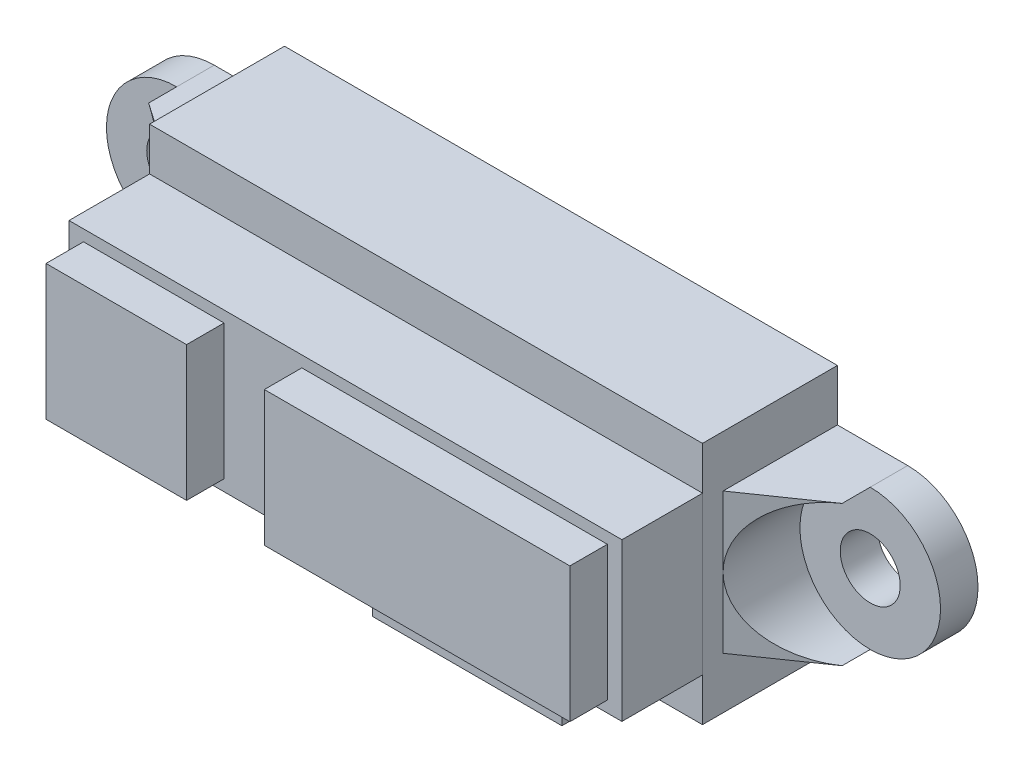
SolidWorks part; units mm, degrees
ref_plane "Front Plane" through (0, 0, 0) normal (0, 0, 1) x (1, 0, 0)
ref_plane "Top Plane" through (0, 0, 0) normal (0, 1, 0) x (1, 0, 0)
ref_plane "Right Plane" through (0, 0, 0) normal (1, 0, 0) x (0, 0, -1)
sketch "Sketch1" plane through (0, 0, 0) normal (0, 0, 1) x (1, 0, 0)
  line L1 (-14.75, 6.5) -> (14.75, 6.5)
  line L2 (-14.75, 6.5) -> (-14.75, -6.5)
  line L3 (-14.75, -6.5) -> (14.75, -6.5)
  line L4 (14.75, 6.5) -> (14.75, -6.5)
  line L5 (-14.75, 6.5) -> (14.75, -6.5) construction
  line L6 (-14.75, -6.5) -> (14.75, 6.5) construction
  point P0 (0, 0)
  dimension "D1" = 13
  dimension "D2" = 29.5
extrude "Boss-Extrude1" add sketch "Sketch1" along normal blind 7.2
sketch "Sketch2" plane through (0, 0, 7.2) normal (0, 0, 1) x (1, 0, 0)
  line L0 (14.75, -6.5) -> (14.75, 6.5) construction
  line L1 (-14.7465, 4.1995) -> (14.7535, 4.1995)
  line L2 (-14.7465, 4.1995) -> (-14.757, -4.2005)
  line L3 (-14.757, -4.2005) -> (14.75, -4.2005)
  line L4 (14.7535, 4.1995) -> (14.75, -4.2005)
  line L5 (-14.7465, 4.1995) -> (14.75, -4.2005) construction
  line L6 (-14.757, -4.2005) -> (14.7535, 4.1995) construction
  point P0 (0, 0)
  dimension "D1" = 29.5
  dimension "D2" = 8.4
extrude "Boss-Extrude2" add sketch "Sketch2" along normal blind 4.3
sketch "Sketch3" plane through (0, 0, 11.5) normal (0, 0, 1) x (1, 0, 0)
  line L1 (-13.975, 3.6) -> (13.975, 3.6) construction
  line L2 (-13.975, 3.6) -> (-13.975, -3.6) construction
  line L3 (-13.975, -3.6) -> (13.975, -3.6) construction
  line L4 (13.975, 3.6) -> (13.975, -3.6) construction
  line L5 (-13.975, 3.6) -> (13.975, -3.6) construction
  line L6 (-13.975, -3.6) -> (13.975, 3.6) construction
  line L7 (-13.975, 3.6) -> (-6.475, 3.6)
  line L8 (-13.975, 3.6) -> (-13.975, -3.6)
  line L9 (-13.975, -3.6) -> (-6.475, -3.6)
  line L10 (-6.475, 3.6) -> (-6.475, -3.6)
  line L11 (13.975, 3.6) -> (-2.325, 3.6)
  line L12 (13.975, 3.6) -> (13.975, -3.6)
  line L13 (13.975, -3.6) -> (-2.325, -3.6)
  line L14 (-2.325, 3.6) -> (-2.325, -3.6)
  point P1 (0, 0)
  dimension "D1" = 7.2
  dimension "D2" = 27.95
  dimension "D3" = 7.5
  dimension "D4" = 16.3
extrude "Boss-Extrude3" add sketch "Sketch3" along normal blind 2
sketch "Sketch4" plane through (0, 0, 0) normal (0, 0, -1) x (-1, 0, 0)
  line L0 (0, 6.5) -> (0, -6.5) construction
  line L1 (-14.75, 6.5) -> (14.75, 6.5) construction
  line L2 (14.75, -6.5) -> (-14.75, -6.5) construction
  line L3 (14.75, 6.5) -> (14.75, -6.5) construction
  line L5 (-14.75, 3.75) -> (-14.75, -3.75)
  line L6 (18.5, 3.75) -> (14.75, 3.75)
  line L7 (-18.5, -3.75) -> (-14.75, -3.75)
  line L8 (18.5, -3.75) -> (14.75, -3.75)
  line L9 (14.75, 3.75) -> (14.75, -3.75)
  line L10 (-18.5, 3.75) -> (-14.75, 3.75)
  arc A0 (18.5, -3.75) -> (18.5, 3.75) centre (18.5, 0) ccw
  arc A1 (-18.5, -3.75) -> (-18.5, 3.75) centre (-18.5, 0) cw
  circle A2 centre (18.5, 0) radius 1.6
  circle A3 centre (-18.5, 0) radius 1.6
  dimension "D2" = 3.75
  dimension "D1" = 7.5
  dimension "D5" = 3.2
  dimension "D3" = 6.5
  dimension "D4" = 7.5
extrude "Boss-Extrude6" add sketch "Sketch4" against normal blind 2
sketch "Sketch6" plane through (0, 0, 0) normal (0, 0, -1) x (-1, 0, 0)
  line L0 (14.75, -6.5) -> (-14.75, -6.5) construction
  line L1 (-5.05, -6.5) -> (5.05, -6.5)
  line L2 (-5.05, -6.5) -> (-5.05, -12.5)
  line L3 (-5.05, -12.5) -> (5.05, -12.5)
  line L4 (5.05, -6.5) -> (5.05, -12.5)
  point P6 (0, -6.5)
  point P7 (0, -6.5)
  dimension "D1" = 10.1
  dimension "D2" = 6
extrude "Boss-Extrude7" add sketch "Sketch6" against normal blind 5
sketch "Sketch7" plane through (0, 0, 2) normal (0, 0, 1) x (1, 0, 0)
  line L1 (-14.75, 3.75) -> (-18.5, 3.75)
  line L2 (-14.75, 3.75) -> (-14.75, -3.75)
  line L3 (-14.75, -3.75) -> (-18.5, -3.75)
  line L4 (-18.5, 3.75) -> (-18.5, -3.75)
  line L5 (0, 6.5141) -> (0, -7.6163) construction
  line L6 (18.5, 3.75) -> (18.5, -3.75)
  line L7 (14.75, -3.75) -> (18.5, -3.75)
  line L8 (14.75, 3.75) -> (14.75, -3.75)
  line L9 (14.75, 3.75) -> (18.5, 3.75)
extrude "Boss-Extrude8" add sketch "Sketch7" along normal blind 4.1
sketch "Sketch8" plane through (0, 0, 6.1) normal (0, 0, 1) x (1, 0, 0)
  line L0 (-18.5, 0) -> (-14.75, 0) construction
  line L1 (-18.5, 3.75) -> (-18.5, -3.75) construction
  line L2 (-14.75, -3.75) -> (-14.75, 3.75) construction
  line L3 (-18.5, 3.75) -> (-18.5, -3.75) construction
  line L4 (14.75, 6.5) -> (-14.75, 6.5) construction
  line L5 (0, 6.6491) -> (0, -6.3225) construction
  line L6 (18.5, 3.75) -> (18.5, -3.75) construction
  line L7 (18.5, 0) -> (14.75, 0) construction
  circle A0 centre (-18.5, 0) radius 3.75
  circle A1 centre (18.5, 0) radius 3.75
  point P13 (0, 6.5)
  dimension "D1" = 7.5
extrude "Cut-Extrude1" cut sketch "Sketch8" against normal blind 4.1
sketch "Sketch9" plane through (0, 3.75, 0) normal (0, 1, 0) x (1, 0, 0)
  line L0 (-18.5, -3.5) -> (-15.0403, -3.5) construction
  line L1 (-18.5, -6.1) -> (-18.5, -2) construction
  line L2 (-22.25, -2) -> (-18.5, -2) construction
  line L3 (-18.5, -3.5) -> (-14.75, -6.1)
  line L4 (-14.75, -6.1) -> (-18.5, -6.1)
  line L5 (-18.5, -6.1) -> (-18.5, -3.5)
  line L6 (0, 0) -> (0, -10.2338) construction
  line L7 (18.5, -6.1) -> (18.5, -3.5)
  line L8 (14.75, -6.1) -> (18.5, -6.1)
  line L9 (18.5, -3.5) -> (14.75, -6.1)
  dimension "D1" = 1.5
extrude "Cut-Extrude2" cut sketch "Sketch9" against normal through all
